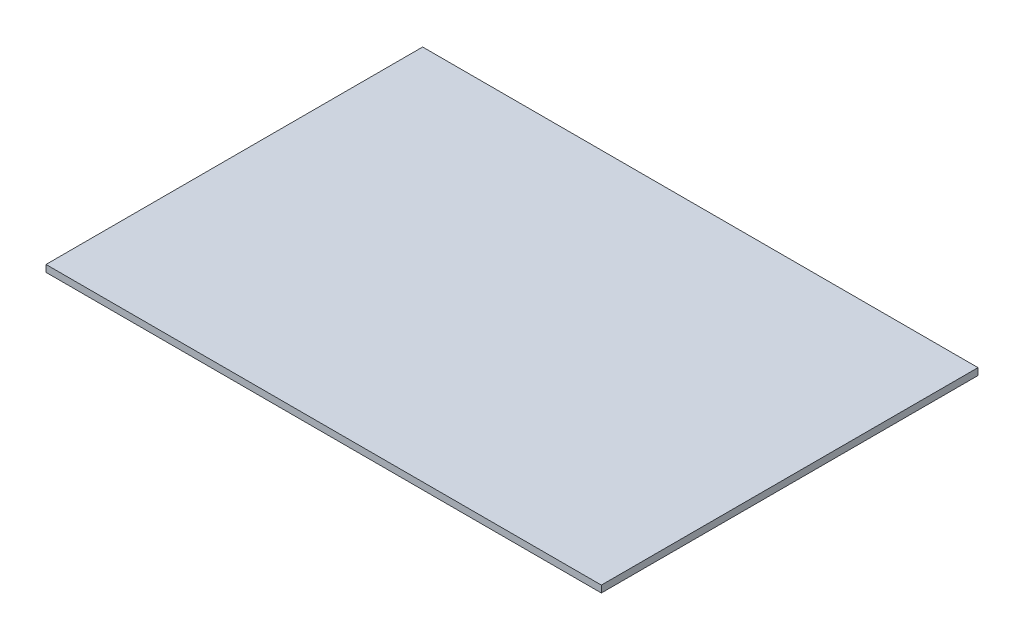
SolidWorks part; units mm, degrees
ref_plane "Front Plane" through (0, 0, 0) normal (0, 0, 1) x (1, 0, 0)
ref_plane "Top Plane" through (0, 0, 0) normal (0, 1, 0) x (1, 0, 0)
ref_plane "Right Plane" through (0, 0, 0) normal (1, 0, 0) x (0, 0, -1)
sketch "Sketch1" plane through (0, 0, 0) normal (0, 1, 0) x (1, 0, 0)
  line L1 (-102.5808, -69.5721) -> (102.5808, -69.5721)
  line L2 (-102.5808, -69.5721) -> (-102.5808, 69.5721)
  line L3 (-102.5808, 69.5721) -> (102.5808, 69.5721)
  line L4 (102.5808, -69.5721) -> (102.5808, 69.5721)
  line L5 (-102.5808, -69.5721) -> (102.5808, 69.5721) construction
  line L6 (-102.5808, 69.5721) -> (102.5808, -69.5721) construction
  point P0 (0, 0)
extrude "Boss-Extrude1" add sketch "Sketch1" along normal blind 2.54
